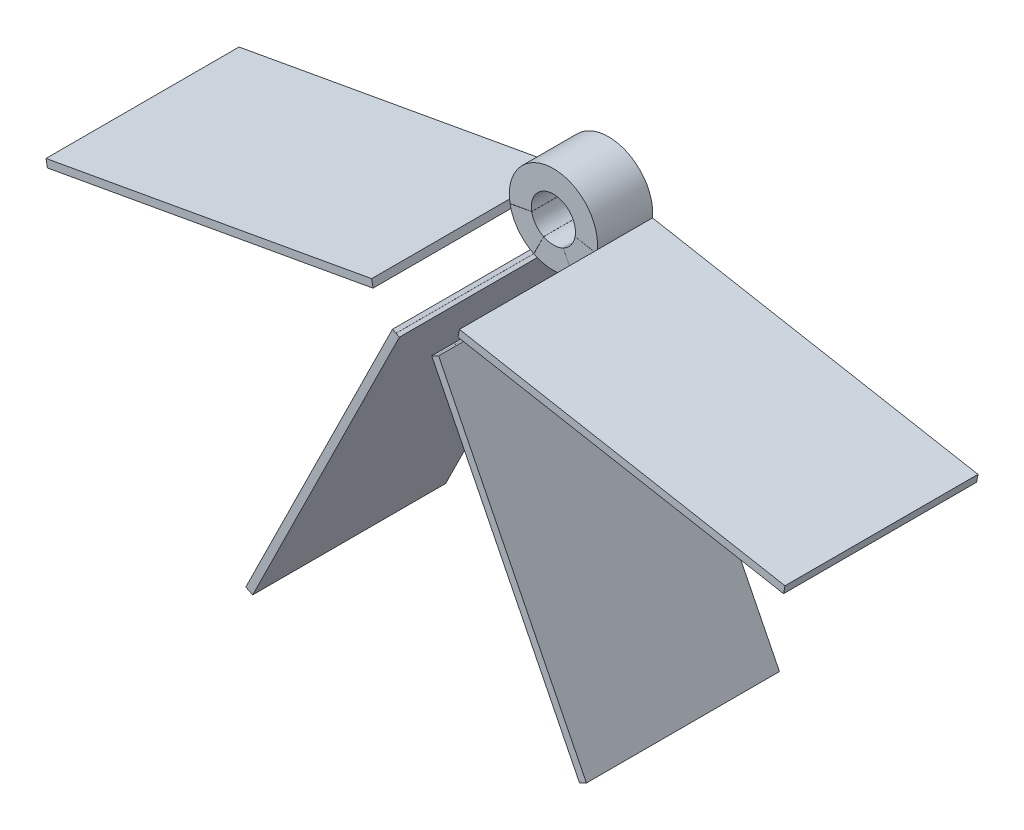
SolidWorks part; units mm, degrees
ref_plane "Front Plane" through (0, 0, 0) normal (0, 0, 1) x (1, 0, 0)
ref_plane "Top Plane" through (0, 0, 0) normal (0, 1, 0) x (1, 0, 0)
ref_plane "Right Plane" through (0, 0, 0) normal (1, 0, 0) x (0, 0, -1)
sketch "Sketch1" plane through (0, 0, 0) normal (0, 0, 1) x (1, 0, 0)
  line L0 (-20, 0) -> (20, 0)
  line L1 (0, 0) -> (-19.6651, -3.6447)
  line L2 (0, 0) -> (19.6651, -3.6447)
  line L3 (0, 0) -> (-8.924, -17.8987)
  line L4 (0, 0) -> (8.924, -17.8987)
  line L5 (0, 0) -> (-19.2726, -5.3448)
  line L6 (0, 0) -> (-7.33, -18.6084)
  line L7 (0, 0) -> (10.45, -17.0528)
  line L8 (0, 0) -> (19.9079, -1.9169)
  line L9 (0, 0) -> (-19.9079, -1.9169)
  line L10 (0, 0) -> (-10.45, -17.0528)
  line L11 (0, 0) -> (7.33, -18.6084)
  line L12 (0, 0) -> (19.2726, -5.3448)
  line L13 (0, 0) -> (-55.96, -10.0883)
  line L14 (-19.9079, -1.9169) -> (-167.5283, -28.5295)
  line L15 (-19.2726, -5.3448) -> (-166.893, -31.9573)
  line L16 (0, 0) -> (-22.0947, -44.6671)
  line L17 (-10.45, -17.0528) -> (-76.9564, -151.5032)
  line L18 (-7.33, -18.6084) -> (-73.8364, -153.0587)
  line L19 (0, 0) -> (21.5905, -43.234)
  line L20 (7.33, -18.6084) -> (74.3461, -152.8054)
  line L21 (10.45, -17.0528) -> (77.4661, -151.2498)
  line L22 (0, 0) -> (59.5269, -10.8463)
  line L23 (19.9079, -1.9169) -> (167.4782, -28.8056)
  line L24 (19.2726, -5.3448) -> (166.8429, -32.2334)
  line L25 (-167.5283, -28.5295) -> (-166.893, -31.9573)
  line L26 (-76.9564, -151.5032) -> (-73.8364, -153.0587)
  line L27 (77.4661, -151.2498) -> (74.3461, -152.8054)
  line L28 (167.4782, -28.8056) -> (166.8429, -32.2334)
  circle A0 centre (0, 0) radius 20
  circle A1 centre (0, 0) radius 10
extrude "Boss-Extrude2" add sketch "Sketch1" along normal blind 25
sketch "Sketch2" plane through (0, 0, 25) normal (0, 0, 1) x (1, 0, 0)
  line L0 (-167.5283, -28.5295) -> (-19.9079, -1.9169)
  line L1 (-19.9079, -1.9169) -> (-19.2726, -5.3448)
  line L2 (-19.2726, -5.3448) -> (-166.893, -31.9573)
  line L3 (-166.893, -31.9573) -> (-167.5283, -28.5295)
extrude "Boss-Extrude3" add sketch "Sketch2" along normal blind 62.5
sketch "Sketch3" plane through (0, 0, 25) normal (0, 0, 1) x (1, 0, 0)
  line L0 (-76.9564, -151.5032) -> (-10.45, -17.0528)
  line L1 (-10.45, -17.0528) -> (-7.33, -18.6084)
  line L2 (-7.33, -18.6084) -> (-73.8364, -153.0587)
  line L3 (-73.8364, -153.0587) -> (-76.9564, -151.5032)
  line L4 (7.33, -18.6084) -> (10.45, -17.0528)
  line L5 (10.45, -17.0528) -> (77.4661, -151.2498)
  line L6 (77.4661, -151.2498) -> (74.3461, -152.8054)
  line L7 (74.3461, -152.8054) -> (7.33, -18.6084)
  line L8 (19.9079, -1.9169) -> (19.2726, -5.3448)
  line L9 (19.9079, -1.9169) -> (167.4782, -28.8056)
  line L10 (167.4782, -28.8056) -> (166.8429, -32.2334)
  line L11 (167.4782, -28.8056) -> (166.8429, -32.2334)
extrude "Boss-Extrude5" add sketch "Sketch3" along normal blind 62.5
